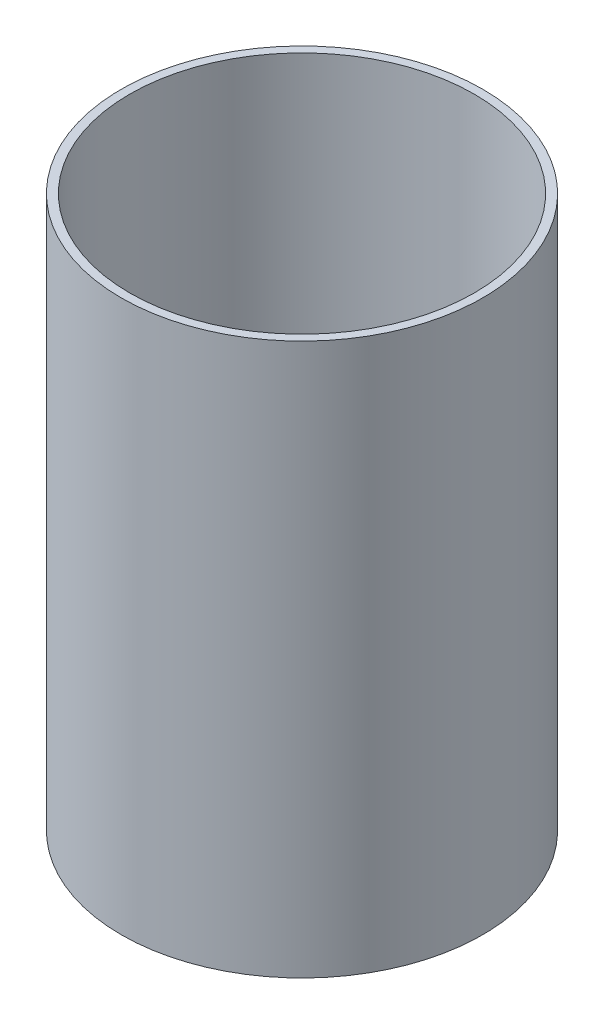
SolidWorks part; units mm, degrees
material "Nickel"
ref_plane "Front Plane" through (0, 0, 0) normal (0, 0, 1) x (1, 0, 0)
ref_plane "Top Plane" through (0, 0, 0) normal (0, 1, 0) x (1, 0, 0)
ref_plane "Right Plane" through (0, 0, 0) normal (1, 0, 0) x (0, 0, -1)
sketch "Sketch2" plane through (0, 0, 0) normal (0, 1, 0) x (1, 0, 0)
  circle A0 centre (0, 0) radius 10.15
  circle A1 centre (0, 0) radius 10.65
  dimension "D1" = 20.3
  dimension "D2" = 0.5
extrude "Boss-Extrude1" add sketch "Sketch2" along normal blind 32.5
